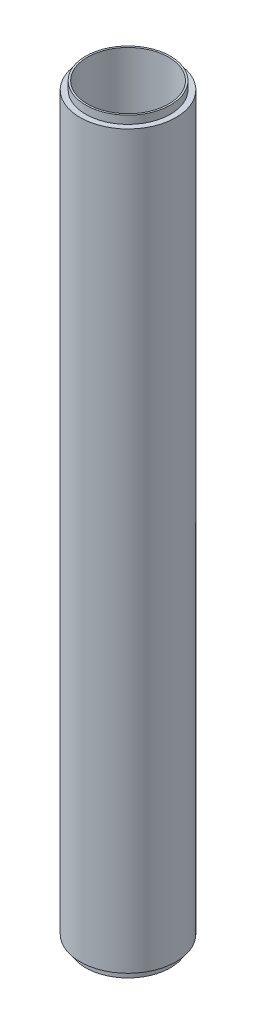
SolidWorks part; units mm, degrees
ref_plane "Front Plane" through (0, 0, 0) normal (0, 0, 1) x (1, 0, 0)
ref_plane "Top Plane" through (0, 0, 0) normal (0, 1, 0) x (1, 0, 0)
ref_plane "Right Plane" through (0, 0, 0) normal (1, 0, 0) x (0, 0, -1)
other "Default"
sketch "Sketch1" plane through (0, 0, 0) normal (0, 0, 1) x (1, 0, 0)
  line L0 (0, -24.2742) -> (0, 16.5291) construction
  line L1 (25.4, -233.6) -> (25.4, 233.6)
  line L2 (25.4, 233.6) -> (26.5, 233.6)
  line L3 (26.5, 233.6) -> (26.5, 228.6)
  line L4 (26.5, 228.6) -> (30, 228.6)
  line L5 (30, 228.6) -> (30, -228.6)
  line L6 (30, -228.6) -> (26.5, -228.6)
  line L7 (26.5, -228.6) -> (26.5, -233.6)
  line L8 (26.5, -233.6) -> (25.4, -233.6)
  point P9 (25.4, 0)
  point P12 (30, 0)
  dimension "ID" = 50.8
  dimension "OD" = 53
  dimension "FilamentD" = 60
  dimension "SideSpacing" = 5
  dimension "TotalLength" = 467.2
revolve "Revolve1" add sketch "Sketch1" angle 360 about L0
